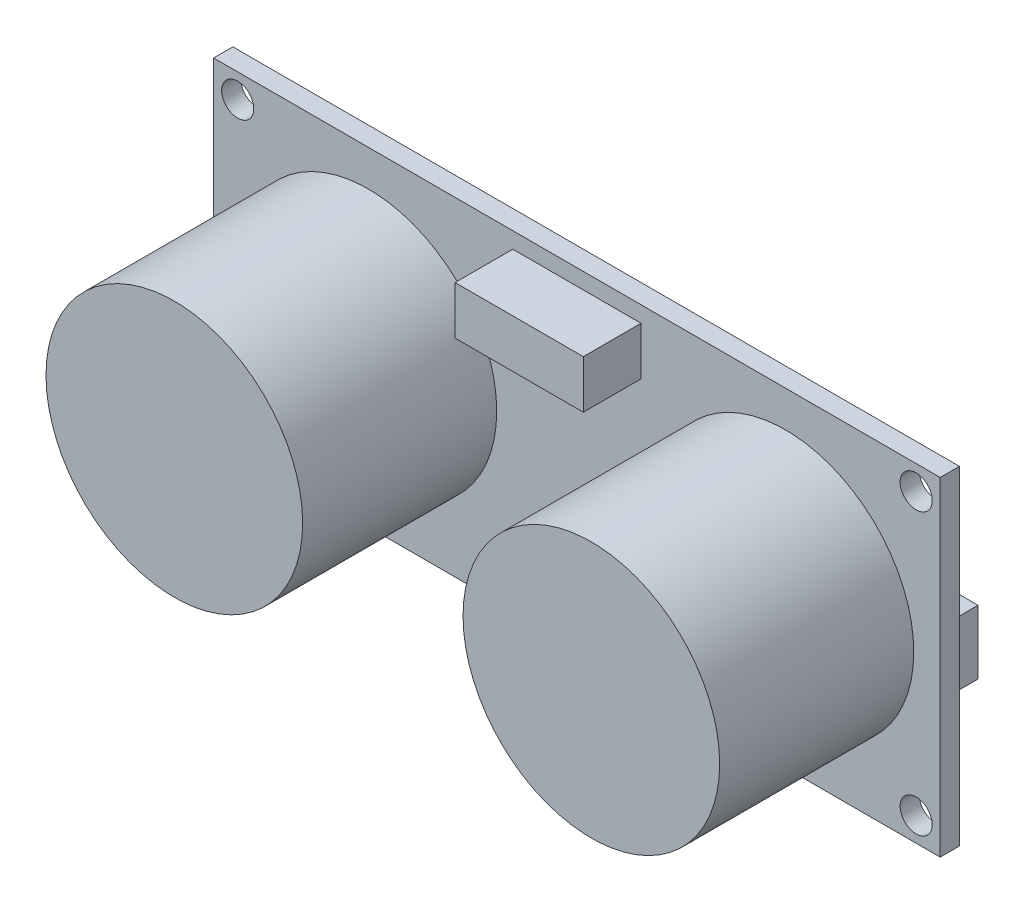
SolidWorks part; units mm, degrees
ref_plane "前视基准面" through (0, 0, 0) normal (0, 0, 1) x (1, 0, 0)
ref_plane "上视基准面" through (0, 0, 0) normal (0, 1, 0) x (1, 0, 0)
ref_plane "右视基准面" through (0, 0, 0) normal (1, 0, 0) x (0, 0, -1)
other "Configuration Table"
sketch "草图1" plane through (0, 0, 0) normal (0, 0, 1) x (1, 0, 0)
  line L0 (0, 0) -> (6.937, 0) construction
  line L1 (-22.65, 10.25) -> (22.65, 10.25)
  line L2 (-22.65, 10.25) -> (-22.65, -10.25)
  line L3 (-22.65, -10.25) -> (22.65, -10.25)
  line L4 (22.65, 10.25) -> (22.65, -10.25)
  line L5 (-22.65, 10.25) -> (22.65, -10.25) construction
  line L6 (-22.65, -10.25) -> (22.65, 10.25) construction
  line L8 (0, 0) -> (0, -7.3823) construction
  circle A0 centre (-13, 0) radius 8
  circle A1 centre (13, 0) radius 8
  circle A2 centre (-21.15, 8.75) radius 1
  circle A3 centre (21.15, 8.75) radius 1
  circle A4 centre (-21.15, -8.75) radius 1
  circle A5 centre (21.15, -8.75) radius 1
  point P0 (0, 0)
  dimension "D3" = 16
  dimension "D4" = 16
  dimension "D5" = 26
  dimension "D6" = 2
  dimension "D7" = 1.5
  dimension "D8" = 1.5
  dimension "D1" = 45.3
  dimension "D2" = 20.5
extrude "凸台-拉伸1" add sketch "草图1" along normal blind 1.2
sketch "草图2" plane through (0, 0, 1.2) normal (0, 0, 1) x (1, 0, 0)
  circle A0 centre (13, 0) radius 8 construction
  circle A1 centre (-13, 0) radius 8 construction
  circle A2 centre (13, 0) radius 8
  circle A3 centre (-13, 0) radius 8
extrude "凸台-拉伸2" add sketch "草图2" along normal blind 13.3 from surface at -1.2 starting at face at (0, 0, 0)
sketch "草图3" plane through (0, 0, 1.2) normal (0, 0, 1) x (1, 0, 0)
  line L1 (-4, 9.25) -> (4, 9.25)
  line L2 (-4, 9.25) -> (-4, 6.25)
  line L3 (-4, 6.25) -> (4, 6.25)
  line L4 (4, 9.25) -> (4, 6.25)
  line L6 (0, 0) -> (0, -4.6711) construction
  line L7 (22.65, 10.25) -> (-22.65, 10.25) construction
  dimension "D1" = 8
  dimension "D2" = 3
  dimension "D3" = 1
extrude "凸台-拉伸3" add sketch "草图3" along normal blind 4.8 from surface at -1.2 starting at face at (0, 0, 0)
sketch "草图5" plane through (0, 0, 0) normal (0, 0, -1) x (-1, 0, 0)
  line L1 (-22.0053, 1.5275) -> (-14.257, 1.5275)
  line L2 (-22.0053, 1.5275) -> (-22.0053, -2.4573)
  line L3 (-22.0053, -2.4573) -> (-14.257, -2.4573)
  line L4 (-14.257, 1.5275) -> (-14.257, -2.4573)
  line L5 (-5.1803, 4.1398) -> (4.3834, 4.1398)
  line L6 (-5.1803, 4.1398) -> (-5.1803, -2.4573)
  line L7 (-5.1803, -2.4573) -> (4.3834, -2.4573)
  line L8 (4.3834, 4.1398) -> (4.3834, -2.4573)
  line L9 (16.2937, 5.9109) -> (21.6068, 5.9109)
  line L10 (16.2937, 5.9109) -> (16.2937, -5.291)
  line L11 (16.2937, -5.291) -> (21.6068, -5.291)
  line L12 (21.6068, 5.9109) -> (21.6068, -5.291)
extrude "凸台-拉伸4" add sketch "草图5" along normal blind 3 from surface at -1.2 starting at face at (-22.15, -8.75, 1.2)
sketch "草图6" plane through (0, 0, 0) normal (0, 0, -1) x (-1, 0, 0)
  line L0 (-4.0319, -8.25) -> (6.3383, -8.25) construction
  line L1 (22.65, -10.25) -> (-22.65, -10.25) construction
  circle A0 centre (-4.0319, -8.25) radius 1.27
  circle A1 centre (-0.4428, -8.25) radius 1.27
  circle A2 centre (2.9075, -8.25) radius 1.27
  circle A3 centre (6.3383, -8.25) radius 1.27
  point P8 (0, 0)
  point P11 (0, 0)
  dimension "D1" = 2.54
  dimension "D2" = 2
extrude "切除-拉伸1" cut sketch "草图6" against normal up to next contours A0
